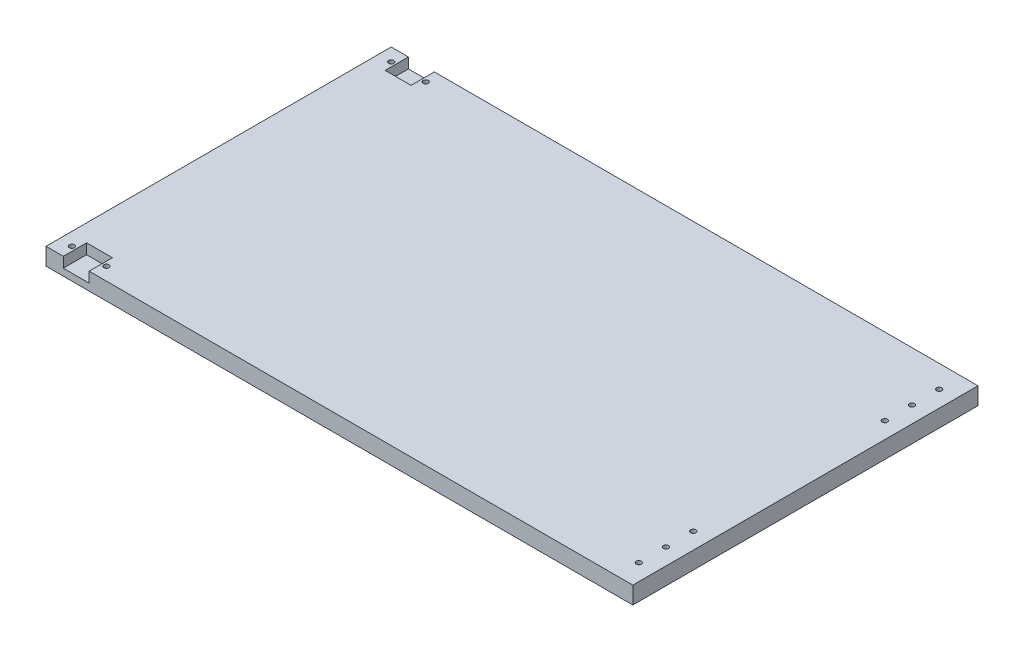
SolidWorks part; units mm, degrees
ref_plane "Front Plane" through (0, 0, 0) normal (0, 0, 1) x (1, 0, 0)
ref_plane "Top Plane" through (0, 0, 0) normal (0, 1, 0) x (1, 0, 0)
ref_plane "Right Plane" through (0, 0, 0) normal (1, 0, 0) x (0, 0, -1)
sketch "Sketch1" plane through (0, 0, 0) normal (0, 1, 0) x (1, 0, 0)
  line L1 (-340, 200) -> (340, 200)
  line L2 (-340, 200) -> (-340, -200)
  line L3 (-340, -200) -> (340, -200)
  line L4 (340, 200) -> (340, -200)
  line L5 (-340, 200) -> (340, -200) construction
  line L6 (-340, -200) -> (340, 200) construction
  point P0 (0, 0)
  dimension "D1" = 680
  dimension "D2" = 400
extrude "Boss-Extrude1" add sketch "Sketch1" along normal blind 20
sketch "Sketch2" plane through (0, 20, 0) normal (0, 1, 0) x (1, 0, 0)
  line L0 (-340, -200) -> (340, -200) construction
  line L1 (-320, -200) -> (-290, -200)
  line L2 (-320, -200) -> (-320, -173)
  line L3 (-320, -173) -> (-290, -173)
  line L4 (-290, -200) -> (-290, -173)
  line L5 (-340, 200) -> (-340, -200) construction
  dimension "D1" = 20
  dimension "D2" = 30
  dimension "D3" = 27
extrude "Cut-Extrude1" cut sketch "Sketch2" against normal blind 12
mirror "Mirror1" about plane through (0, 0, 0) normal (0, 0, 1) of "Cut-Extrude1"
sketch "Sketch3" plane through (0, 20, 0) normal (0, 1, 0) x (1, 0, 0)
  circle A0 centre (321, -174) radius 3
  circle A1 centre (321, -142.5) radius 3
  circle A2 centre (321, -111) radius 3
  dimension "D4" = 6
extrude "Cut-Extrude2" cut sketch "Sketch3" against normal blind 13
mirror "Mirror2" about plane through (0, 0, 0) normal (0, 0, 1) of "Cut-Extrude2"
sketch "Sketch4" plane through (0, 20, 0) normal (0, 1, 0) x (1, 0, 0)
  line L0 (-340, 200) -> (-340, -200) construction
  line L1 (-340, -200) -> (-320, -200) construction
  line L2 (-290, -200) -> (-290, -173) construction
  circle A0 centre (-325, -185) radius 3
  circle A1 centre (-285, -185) radius 3
  dimension "D1" = 6
  dimension "D2" = 15
  dimension "D3" = 15
  dimension "D4" = 5
extrude "Cut-Extrude3" cut sketch "Sketch4" against normal blind 13
mirror "Mirror3" about plane through (0, 0, 0) normal (0, 0, 1) of "Cut-Extrude3"
